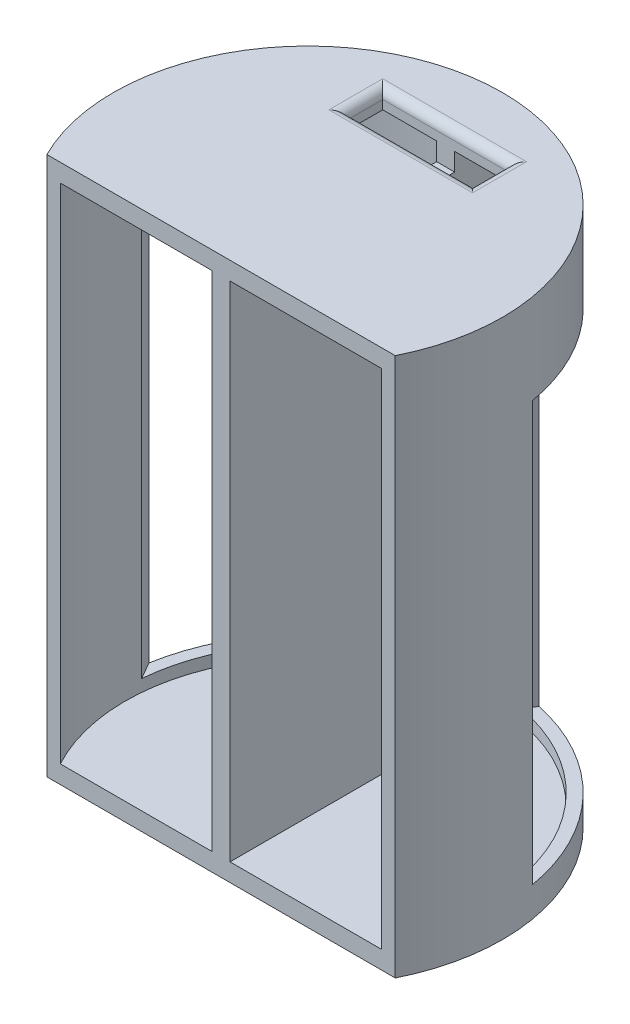
SolidWorks part; units mm, degrees
ref_plane "Front Plane" through (0, 0, 0) normal (0, 0, 1) x (1, 0, 0)
ref_plane "Top Plane" through (0, 0, 0) normal (0, 1, 0) x (1, 0, 0)
ref_plane "Right Plane" through (0, 0, 0) normal (1, 0, 0) x (0, 0, -1)
sketch "Sketch1" plane through (0, 0, 0) normal (0, 1, 0) x (1, 0, 0)
  circle A0 centre (0, 0) radius 32.5
  circle A1 centre (0, 0) radius 30.5
  dimension "D1" = 65
  dimension "D2" = 2
extrude "CYLINDER BULK EXTRUDE" add sketch "Sketch1" along normal blind 90
sketch "Sketch2" plane through (0, 90, 0) normal (0, 1, 0) x (1, 0, 0)
  circle A0 centre (0, 0) radius 32.5 construction
  circle A1 centre (0, 0) radius 32.5
extrude "TOP LID" add sketch "Sketch2" against normal blind 3
sketch "Sketch3" plane through (0, 0, 0) normal (0, -1, 0) x (1, 0, 0)
  circle A0 centre (0, 0) radius 32.5 construction
  circle A1 centre (0, 0) radius 32.5
extrude "BOTTOM LID" add sketch "Sketch3" against normal blind 3
sketch "Sketch5" plane through (0, 90, 0) normal (0, 1, 0) x (1, 0, 0)
  line L1 (-29.0861, -14.5) -> (29.0861, -14.5)
  line L2 (-29.0861, -14.5) -> (-29.0861, -32.5)
  line L3 (-29.0861, -32.5) -> (29.0861, -32.5)
  line L4 (29.0861, -14.5) -> (29.0861, -32.5)
  circle A0 centre (0, 0) radius 32.5 construction
  dimension "D1" = 18
extrude "REAR ACCESS CUT" cut sketch "Sketch5" against normal through all both and the other way through all
sketch "AXIS" plane through (0, 0, 0) normal (1, 0, 0) x (0, 0, -1)
  line L0 (0, 0) -> (0, 90)
  line L1 (32.5, 90) -> (-14.5, 90) construction
ref_plane "Plane1" through (0, 0, 0) normal (0.5, 0, -0.866) x (0, 1, 0)
sketch "Sketch8" plane through (0, 0, 0) normal (0.5, 0, -0.866) x (0, 1, 0)
  line L1 (5, 25) -> (75, 25)
  line L2 (5, 25) -> (5, -10)
  line L3 (5, -10) -> (75, -10)
  line L4 (75, 25) -> (75, -10)
  point P4 (40, -10)
  point P6 (5, -12.2241)
  dimension "D1" = 25
  dimension "D2" = 70
  dimension "D3" = 40
  dimension "D4" = 10
extrude "WEIGHT RELIEF PT1" cut sketch "Sketch8" against normal through all both and the other way through all
mirror "WEIGHT RELIEF PT2" about plane through (0, 0, 0) normal (1, 0, 0) of "WEIGHT RELIEF PT1"
sketch "Sketch6" plane through (0, 0, 14.5) normal (0, 0, 1) x (1, 0, 0)
  line L0 (29.0861, 90) -> (-29.0861, 90) construction
  line L1 (-1.5, 90) -> (1.5, 90)
  line L2 (-1.5, 90) -> (-1.5, 0)
  line L3 (-1.5, 0) -> (1.5, 0)
  line L4 (1.5, 90) -> (1.5, 0)
  line L5 (29.0861, 0) -> (-29.0861, 0) construction
  point P8 (0, 0)
  dimension "D1" = 3
extrude "CENTER STIFFNESS RIB" add sketch "Sketch6" against normal up to next
sketch "Sketch4" plane through (0, 90, 0) normal (0, 1, 0) x (1, 0, 0)
  line L1 (-10.5, 23) -> (10.5, 23)
  line L2 (-10.5, 23) -> (-10.5, 17)
  line L3 (-10.5, 17) -> (10.5, 17)
  line L4 (10.5, 23) -> (10.5, 17)
  point P5 (0, 17)
  dimension "D1" = 17
  dimension "D2" = 6
  dimension "D3" = 21
extrude "ALIGNMENT SLOT CUT" cut sketch "Sketch4" against normal blind 6 and the other way through all
fillet "Fillet1" radius 1.5 4 edges at (0, 90, -17) (10.5, 90, -20) (-10.5, 90, -20) (0, 90, -23)
sketch "Sketch9" plane through (0, 0, 0) normal (0, -1, 0) x (1, 0, 0)
  line L1 (-10, -17.5) -> (10, -17.5)
  line L2 (-10, -17.5) -> (-10, -22.5)
  line L3 (-10, -22.5) -> (10, -22.5)
  line L4 (10, -17.5) -> (10, -22.5)
  point P4 (0, -17.5)
  dimension "D1" = 17.5
  dimension "D2" = 5
  dimension "D3" = 20
extrude "ALIGNMENT PEG" add sketch "Sketch9" along normal blind 5
fillet "Fillet2" radius 1 4 edges at (0, 0, -17.5) (10, 0, -20) (-10, 0, -20) (0, 0, -22.5)
